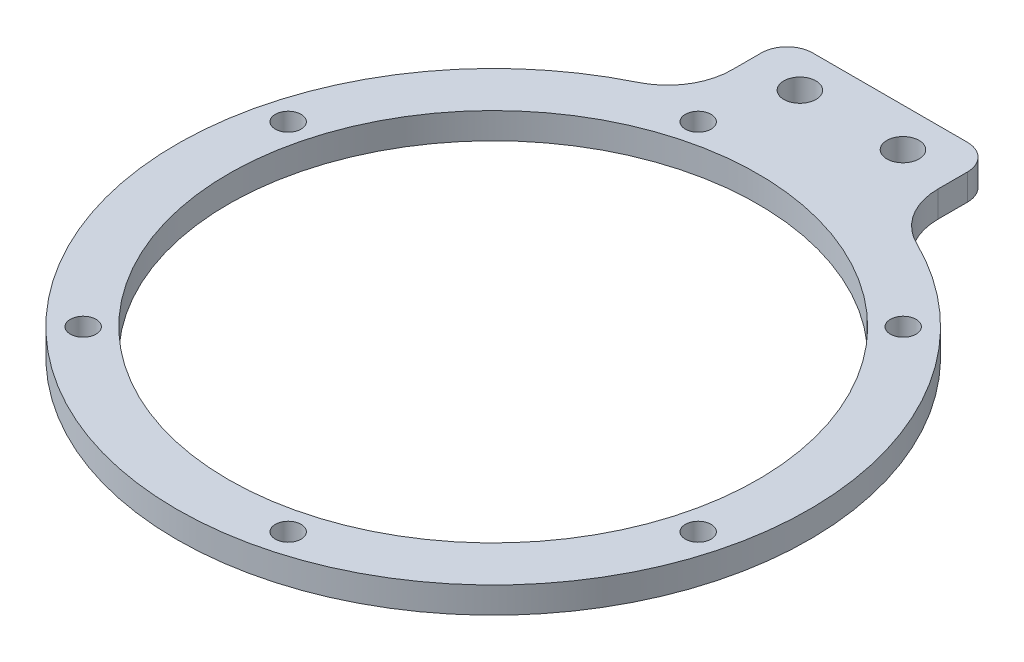
SolidWorks part; units mm, degrees
ref_plane "Front Plane" through (0, 0, 0) normal (0, 0, 1) x (1, 0, 0)
ref_plane "Top Plane" through (0, 0, 0) normal (0, 1, 0) x (1, 0, 0)
ref_plane "Right Plane" through (0, 0, 0) normal (1, 0, 0) x (0, 0, -1)
sketch "Sketch1" plane through (0, 0, 0) normal (0, 1, 0) x (1, 0, 0)
  line L0 (-16, 46.4199) -> (-16, 61.6)
  line L4 (-11.6469, 43.4667) -> (0, 0) construction
  line L5 (0, 0) -> (0, 49.1) construction
  line L6 (-16, 61.6) -> (16, 61.6)
  line L7 (-8, 55.6) -> (8, 55.6) construction
  line L8 (16, 61.6) -> (16, 46.4199)
  line L9 (0, 61.6) -> (0, 49.1) construction
  arc A0 (-16, 46.4199) -> (16, 46.4199) centre (0, 0) ccw
  circle A1 centre (0, 0) radius 41.1
  circle A2 centre (-11.6469, 43.4667) radius 2
  circle A3 centre (31.8198, 31.8198) radius 2
  circle A4 centre (43.4667, -11.6469) radius 2
  circle A5 centre (11.6469, -43.4667) radius 2
  circle A6 centre (-31.8198, -31.8198) radius 2
  circle A7 centre (-43.4667, 11.6469) radius 2
  circle A13 centre (-8, 55.6) radius 2.5
  circle A14 centre (8, 55.6) radius 2.5
  arc A15 (16, 46.4199) -> (-16, 46.4199) centre (0, 0) ccw construction
  circle A16 centre (0, 0) radius 45 construction
  point P5 (0, -49.1)
  point P8 (0, 55.6)
  point P25 (0, 49.1)
  point P29 (0, 0)
  dimension "D3" = 98.2
  dimension "D4" = 82.2
  dimension "D5" = 4
  dimension "D10" = 32
  dimension "D14" = 5
  dimension "D9" = 6.5
  dimension "D2" = 6
  dimension "D6" = 45
  dimension "D7" = 15
  dimension "D15" = 16
  dimension "D8" = 6
extrude "Boss-Extrude2" add sketch "Sketch1" along normal blind 4.064
chamfer "Chamfer2" [suppressed] distance 1.7 angle 45
fillet "Fillet1" radius 4 2 edges at (-16, 2.032, -61.6) (16, 2.032, -61.6)
fillet "Fillet2" radius 10 1 edges at (-16, 2.032, -46.4199)
